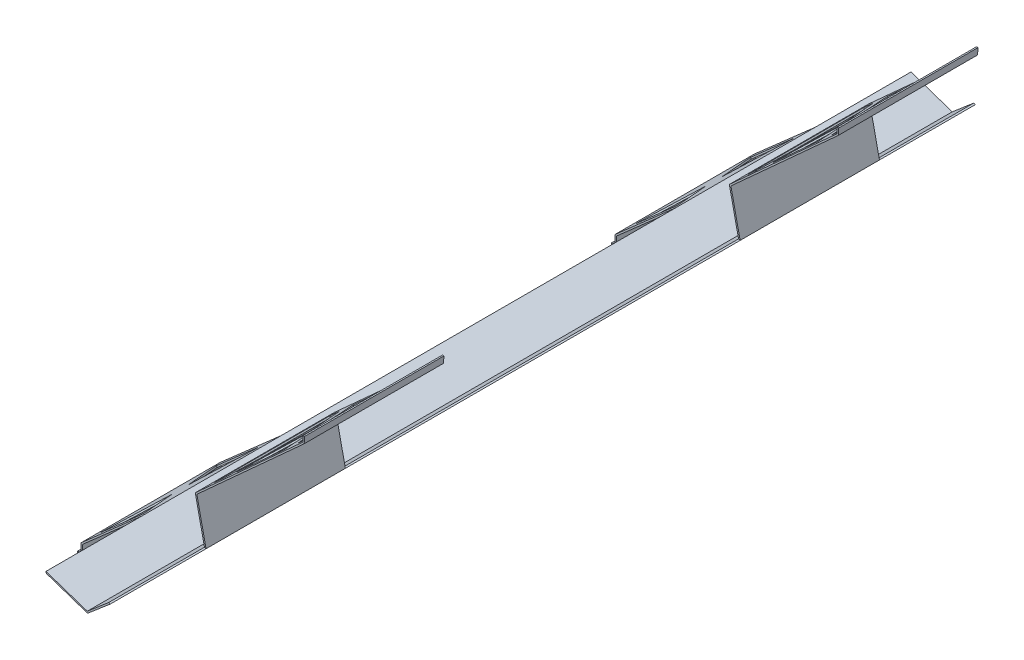
SolidWorks part; units mm, degrees
ref_plane "Front Plane" through (0, 0, 0) normal (0, 0, 1) x (1, 0, 0)
ref_plane "Top Plane" through (0, 0, 0) normal (0, 1, 0) x (1, 0, 0)
ref_plane "Right Plane" through (0, 0, 0) normal (1, 0, 0) x (0, 0, -1)
sketch "Sketch1" plane through (0, 0, 0) normal (0, 0, 1) x (1, 0, 0)
  line L0 (11, 5) -> (11, 55)
  line L1 (11, 55) -> (221.0953, 240.0945)
  line L2 (221.0953, 240.0945) -> (363.2439, 192.2013)
  line L3 (363.2439, 192.2013) -> (437.033, 255.0541)
  line L4 (437.033, 255.0541) -> (405.2784, 401.6544)
  line L5 (405.2784, 401.6544) -> (775.5525, 737.656)
  line L11 (442.5532, 253.1881) -> (364.3307, 186.559)
  line L12 (364.3307, 186.559) -> (222.2345, 234.4345)
  line L13 (222.2345, 234.4345) -> (16, 52.7414)
  line L14 (16, 52.7414) -> (16, 0)
  line L16 (11, 5) -> (5, 5)
  line L20 (5, 5) -> (5, 25)
  line L21 (5, 25) -> (0, 25)
  line L22 (0, 25) -> (0, 0)
  line L23 (0, 0) -> (16, 0)
  line L24 (410.7762, 399.8915) -> (442.5532, 253.1881)
  line L25 (775.5525, 737.656) -> (777.0074, 758.3825)
  line L26 (777.0074, 758.3825) -> (782.0074, 758.3536)
  line L28 (782.0074, 758.3536) -> (780.5793, 735.4658)
  line L29 (410.7762, 399.8915) -> (780.5793, 735.4658)
  dimension "D1" = 5
  dimension "D2" = 5
  dimension "D3" = 5
  dimension "D4" = 5
  dimension "D5" = 5
  dimension "D6" = 120
  dimension "D7" = 120
  dimension "D8" = 5
  dimension "D9" = 280
  dimension "D10" = 500
  dimension "D11" = 245
  dimension "D12" = 150
  dimension "D13" = 5
  dimension "D14" = 150
  dimension "D15" = 6
  dimension "D16" = 50
  dimension "D17" = 25
extrude "Boss-Extrude1" add sketch "Sketch1" along normal blind 480
sketch "Sketch3" plane through (0, 0, 480) normal (0, 0, 1) x (1, 0, 0)
  line L0 (221.0953, 240.0945) -> (363.2439, 192.2013)
  line L1 (363.2439, 192.2013) -> (437.033, 255.0541)
  line L5 (442.5532, 253.1881) -> (364.3307, 186.559)
  line L6 (364.3307, 186.559) -> (222.2345, 234.4345)
  line L7 (222.2345, 234.4345) -> (221.0953, 240.0945)
  line L8 (437.033, 255.0541) -> (442.5532, 253.1881)
extrude "Boss-Extrude2" add sketch "Sketch3" along normal blind 1360 and the other way blind 810
sketch "Sketch4" plane through (0, 0, 1840) normal (0, 0, 1) x (1, 0, 0)
  line L0 (0, 25) -> (5, 25)
  line L1 (5, 25) -> (5, 5)
  line L2 (5, 5) -> (11, 5)
  line L3 (11, 5) -> (11, 55)
  line L4 (11, 55) -> (221.0953, 240.0945)
  line L5 (221.0953, 240.0945) -> (363.2439, 192.2013)
  line L6 (363.2439, 192.2013) -> (437.033, 255.0541)
  line L7 (437.033, 255.0541) -> (405.2784, 401.6544)
  line L8 (405.2784, 401.6544) -> (775.5525, 737.656)
  line L9 (775.5525, 737.656) -> (777.0074, 758.3825)
  line L10 (777.0074, 758.3825) -> (782.0074, 758.3536)
  line L11 (782.0074, 758.3536) -> (780.5793, 735.4658)
  line L12 (780.5793, 735.4658) -> (410.7762, 399.8915)
  line L13 (410.7762, 399.8915) -> (442.5532, 253.1881)
  line L14 (442.5532, 253.1881) -> (364.3307, 186.559)
  line L15 (364.3307, 186.559) -> (222.2345, 234.4345)
  line L16 (222.2345, 234.4345) -> (16, 52.7414)
  line L17 (16, 52.7414) -> (16, 0)
  line L18 (16, 0) -> (0, 0)
  line L19 (0, 0) -> (0, 25)
extrude "Boss-Extrude3" add sketch "Sketch4" along normal blind 480
sketch "Sketch5" plane through (0, 0, 2320) normal (0, 0, 1) x (1, 0, 0)
  line L0 (221.0953, 240.0945) -> (363.2439, 192.2013)
  line L1 (363.2439, 192.2013) -> (437.033, 255.0541)
  line L2 (437.033, 255.0541) -> (442.5532, 253.1881)
  line L3 (442.5532, 253.1881) -> (364.3307, 186.559)
  line L4 (364.3307, 186.559) -> (222.2345, 234.4345)
  line L5 (222.2345, 234.4345) -> (221.0953, 240.0945)
extrude "Boss-Extrude4" add sketch "Sketch5" along normal blind 330
sketch "Sketch8" plane through (-16.8646, 18.5848, 0) normal (-0.672, 0.7405, 0) x (0.7405, 0.672, 0)
  line L0 (710.0636, -40) -> (930.0188, -40)
  line L2 (820.0412, -230.4868) -> (710.0636, -40)
  line L3 (1070.0412, 0) -> (570.0412, 0) construction
  line L4 (820.0412, 53.7156) -> (820.0412, -561.4179) construction
  line L5 (570.0412, -480) -> (570.0412, 0) construction
  line L7 (570.0412, -240) -> (1070.0412, -240) construction
  line L8 (1070.0412, -480) -> (1070.0412, 0) construction
  line L9 (780.5604, -240) -> (647.1054, -39.4975)
  line L10 (647.1054, -39.4975) -> (600.4556, -39.4975)
  line L11 (600.4556, -39.4975) -> (600.4556, -440.5025)
  line L12 (820.0412, -230.4868) -> (930.0188, -40)
  line L13 (859.522, -240) -> (992.977, -39.4975)
  line L14 (992.977, -39.4975) -> (1039.6268, -39.4975)
  line L15 (1039.6268, -39.4975) -> (1039.6268, -440.5025)
  line L16 (992.977, -440.5025) -> (1039.6268, -440.5025)
  line L17 (859.522, -240) -> (992.977, -440.5025)
  line L18 (820.0412, -249.5132) -> (930.0188, -440)
  line L19 (820.0412, -249.5132) -> (710.0636, -440)
  line L20 (710.0636, -440) -> (930.0188, -440)
  line L21 (647.1054, -440.5025) -> (600.4556, -440.5025)
  line L22 (780.5604, -240) -> (647.1054, -440.5025)
  line L29 (80.5575, -440) -> (279.9346, -440)
  line L30 (279.9346, -440) -> (180.246, -267.3344)
  line L31 (180.246, -267.3344) -> (80.5575, -440)
  line L32 (570.0412, -240) -> (45.1062, -240) construction
  line L33 (45.1062, -480) -> (45.1062, 0) construction
  line L34 (80.5575, -40) -> (279.9346, -40)
  line L35 (180.246, -212.6656) -> (80.5575, -40)
  line L36 (279.9346, -40) -> (180.246, -212.6656)
  line L37 (-555.546, -1160) -> (1698.5242, -1160) construction
  line L38 (1070.0412, -480) -> (570.0412, -480) construction
  line L39 (1070.0412, -1840) -> (570.0412, -1840) construction
  line L40 (710.0636, -1880) -> (930.0188, -1880)
  line L41 (820.0412, -2070.4868) -> (710.0636, -1880)
  line L42 (820.0412, -2070.4868) -> (930.0188, -1880)
  line L43 (992.977, -1879.4975) -> (1039.6268, -1879.4975)
  line L44 (992.977, -2280.5025) -> (1039.6268, -2280.5025)
  line L45 (1039.6268, -2280.5025) -> (1039.6268, -1879.4975)
  line L58 (859.522, -2080) -> (992.977, -2280.5025)
  line L59 (859.522, -2080) -> (992.977, -1879.4975)
  line L60 (820.0412, -2089.5132) -> (930.0188, -2280)
  line L61 (710.0636, -2280) -> (930.0188, -2280)
  line L62 (820.0412, -2089.5132) -> (710.0636, -2280)
  line L63 (780.5604, -2080) -> (647.1054, -1879.4975)
  line L64 (647.1054, -1879.4975) -> (600.4556, -1879.4975)
  line L65 (600.4556, -2280.5025) -> (600.4556, -1879.4975)
  line L66 (647.1054, -2280.5025) -> (600.4556, -2280.5025)
  line L67 (780.5604, -2080) -> (647.1054, -2280.5025)
  line L68 (80.5575, -1880) -> (279.9346, -1880)
  line L69 (279.9346, -1880) -> (180.246, -2052.6656)
  line L70 (180.246, -2052.6656) -> (80.5575, -1880)
  line L71 (279.9346, -2280) -> (180.246, -2107.3344)
  line L72 (80.5575, -2280) -> (279.9346, -2280)
  line L73 (180.246, -2107.3344) -> (80.5575, -2280)
  point P18 (820.0412, -40)
  point P23 (1039.6268, -240)
  point P29 (600.4556, -240)
  dimension "D1" = 40
  dimension "D2" = 60
  dimension "D3" = 60
  dimension "D4" = 250
  dimension "D5" = 60
  dimension "D6" = 680
  dimension "D7" = 680
extrude "Cut-Extrude1" cut sketch "Sketch8" against normal blind 30 and the other way blind 10
